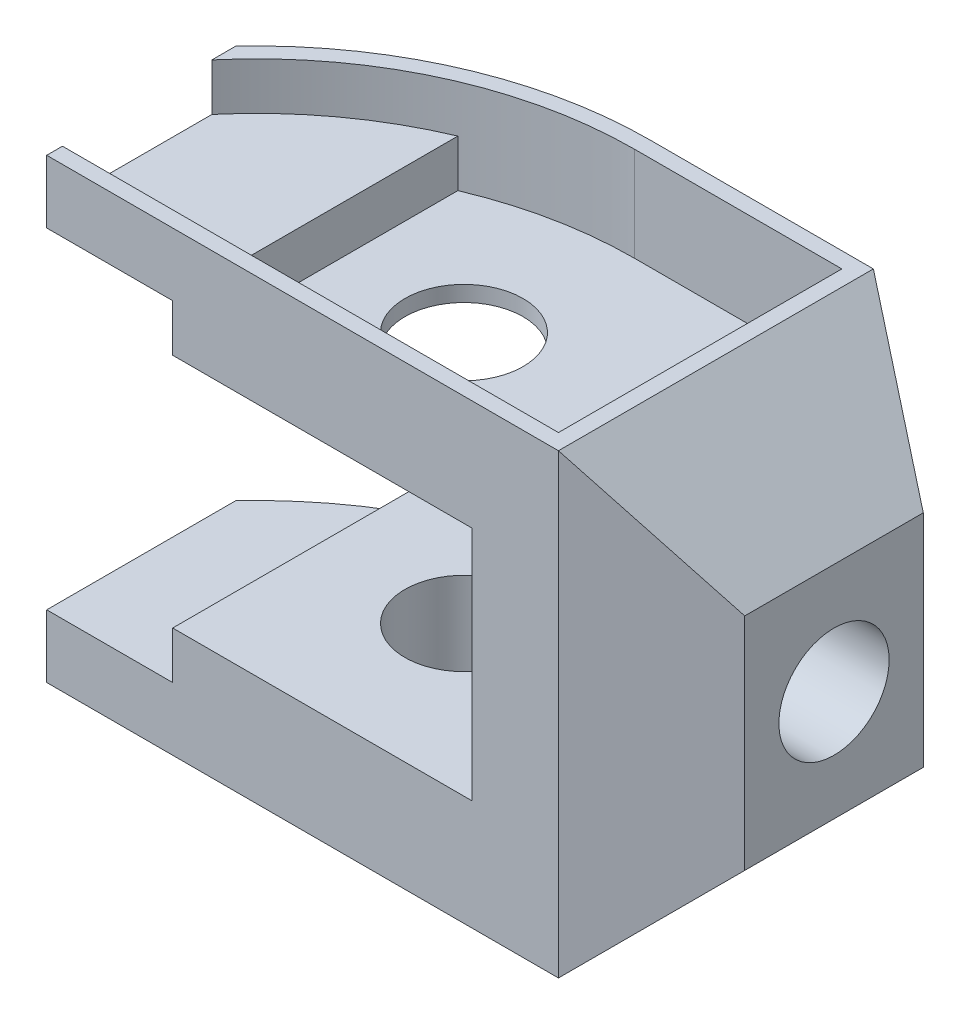
SolidWorks part; units mm, degrees
material "1060 Alloy"
ref_plane "Front Plane" through (0, 0, 0) normal (0, 0, 1) x (1, 0, 0)
ref_plane "Top Plane" through (0, 0, 0) normal (0, 1, 0) x (1, 0, 0)
ref_plane "Right Plane" through (0, 0, 0) normal (1, 0, 0) x (0, 0, -1)
sketch "Sketch1" plane through (0, 0, 0) normal (0, 1, 0) x (1, 0, 0)
  line L0 (0, 0) -> (65, 0)
  line L1 (65, 0) -> (80, 8.6603)
  line L2 (80, 8.6603) -> (80, 31.3397)
  line L3 (80, 31.3397) -> (65, 40)
  line L4 (65, 40) -> (36.6606, 40)
  line L5 (0, 0) -> (0, 24)
  arc A0 (0, 24) -> (36.6606, 40) centre (36.6606, -10) cw
  circle A1 centre (34, 19) radius 7.5
  dimension "D7" = 50
  dimension "D9" = 15
  dimension "D1" = 65
  dimension "D2" = 30
  dimension "D3" = 30
  dimension "D4" = 15
  dimension "D5" = 15
  dimension "D6" = 40
  dimension "D8" = 24
  dimension "D10" = 19
  dimension "D11" = 31
extrude "Boss-Extrude1" add sketch "Sketch1" along normal blind 58
sketch "Sketch2" plane through (0, 0, 0) normal (0, 0, 1) x (1, 0, 0)
  line L0 (0, 50) -> (16, 50)
  line L1 (0, 58) -> (0, 0) construction
  line L2 (16, 50) -> (16, 44)
  line L3 (16, 44) -> (54, 44)
  line L4 (54, 44) -> (54, 14)
  line L5 (54, 14) -> (16, 14)
  line L6 (16, 14) -> (16, 8)
  line L7 (16, 8) -> (0, 8)
  line L8 (0, 8) -> (0, 50)
  line L9 (0, 58) -> (65, 58) construction
  line L10 (65, 58) -> (65, 0) construction
  line L11 (0, 0) -> (65, 0) construction
  dimension "D1" = 8
  dimension "D2" = 6
  dimension "D3" = 11
  dimension "D4" = 16
  dimension "D5" = 8
extrude "Cut-Extrude1" cut sketch "Sketch2" against normal through all
sketch "Sketch4" plane through (0, 0, 0) normal (0, 0, 1) x (1, 0, 0)
  line L0 (65, 58) -> (80, 43)
  line L1 (80, 58) -> (80, 0) construction
  line L2 (80, 43) -> (80, 58)
  line L3 (80, 58) -> (65, 58)
  line L4 (65, 0) -> (80, 0)
  line L5 (80, 0) -> (80, 15)
  line L6 (80, 15) -> (65, 0)
  dimension "D1" = 45
  dimension "D2" = 45
extrude "Cut-Extrude2" cut sketch "Sketch4" against normal through all
sketch "Sketch5" plane through (80, 0, 0) normal (1, 0, 0) x (0, 0, -1)
  line L0 (40, 58) -> (40, 0) construction
  line L1 (40, 0) -> (0, 0) construction
  circle A0 centre (20, 29) radius 7
  dimension "D1" = 14
  dimension "D2" = 20
  dimension "D3" = 29
extrude "Cut-Extrude3" cut sketch "Sketch5" against normal through all
sketch "Sketch8" plane through (0, 58, 0) normal (0, 1, 0) x (1, 0, 0)
  line L0 (0, 24) -> (0, 0) construction
  line L1 (0, 2) -> (0, 20.9839)
  line L8 (2, 2) -> (63, 2)
  line L9 (63, 2) -> (63, 38)
  line L10 (63, 38) -> (36.6606, 38)
  line L11 (2, 23.2061) -> (2, 2)
  line L13 (0, 2) -> (63, 2)
  line L14 (63, 2) -> (63, 38)
  line L22 (63, 38) -> (36.6606, 38)
  arc A2 (36.6606, 38) -> (2, 23.2061) centre (36.6606, -10) ccw
  arc A5 (36.6606, 38) -> (0, 20.9839) centre (36.6606, -10) ccw
  point P6 (0, 0)
  point P8 (0, 0)
  point P9 (18, 4.2817)
  point P11 (0, 0)
  point P12 (0, 0)
  point P14 (0, 20.9839)
  dimension "D1" = 2
extrude "Cut-Extrude4" cut sketch "Sketch8" along direction (0, -1, 0) on the side against the normal offset from surface (6 mm away) 2
sketch "Sketch9" plane through (0, 52, 0) normal (0, 1, 0) x (1, 0, 0)
  line L4 (0, 2) -> (0, 20.9839) construction
  line L8 (0, 2) -> (63, 2)
  line L9 (63, 2) -> (63, 38)
  line L10 (63, 38) -> (36.6606, 38)
  line L11 (0, 20.9839) -> (0, 2)
  line L12 (18, 2) -> (63, 2)
  line L13 (63, 2) -> (63, 38)
  line L14 (63, 38) -> (36.6606, 38)
  line L15 (18, 34.2242) -> (18, 2)
  arc A2 (36.6606, 38) -> (0, 20.9839) centre (36.6606, -10) ccw
  arc A3 (36.6606, 38) -> (18, 34.2242) centre (36.6606, -10) ccw
  dimension "D2" = 18
  dimension "D1" = 0
extrude "Cut-Extrude5" cut sketch "Sketch9" against normal offset from surface (6 mm away) 2 up to face at (34, 44, -11.5)
equation "\"a\"= 58mm"
equation "\"b\"= 40mm"
equation "\"c\"= 65mm"
